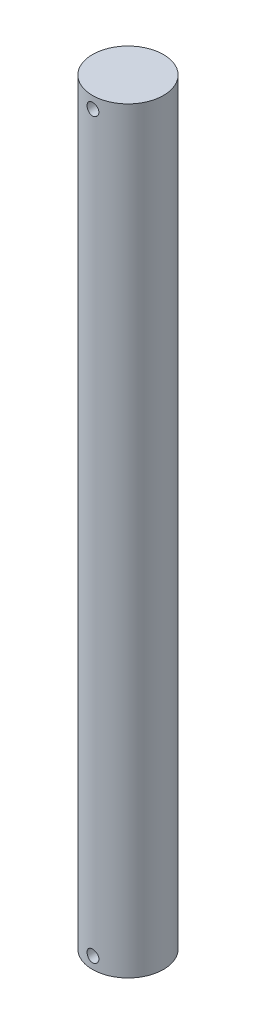
SolidWorks part; units mm, degrees
ref_plane "Front Plane" through (0, 0, 0) normal (0, 0, 1) x (1, 0, 0)
ref_plane "Top Plane" through (0, 0, 0) normal (0, 1, 0) x (1, 0, 0)
ref_plane "Right Plane" through (0, 0, 0) normal (1, 0, 0) x (0, 0, -1)
sketch "Sketch1" plane through (0, 0, 0) normal (0, 1, 0) x (1, 0, 0)
  circle A0 centre (0, 0) radius 30
  dimension "D1" = 60
extrude "Boss-Extrude1" add sketch "Sketch1" along normal blind 640
sketch "Sketch2" plane through (0, 0, 0) normal (0, 0, 1) x (1, 0, 0)
  line L1 (30, 640) -> (-30, 640) construction
  circle A0 centre (0, 630) radius 5
  circle A1 centre (0, 10) radius 5
  dimension "D1" = 10
  dimension "D2" = 10
  dimension "D3" = 10
  dimension "D4" = 10
extrude "Cut-Extrude1" cut sketch "Sketch2" against normal through all both and the other way through all
